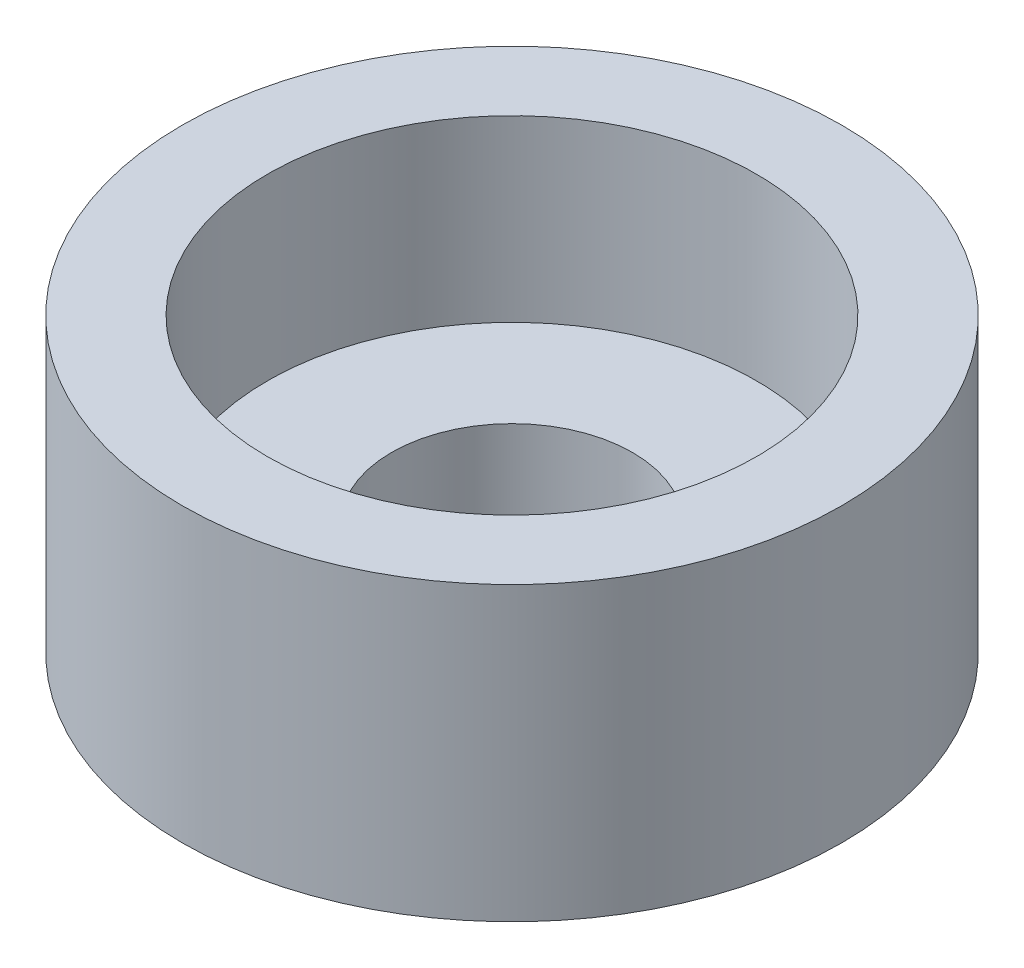
SolidWorks part; units mm, degrees
ref_plane "Front Plane" through (0, 0, 0) normal (0, 0, 1) x (1, 0, 0)
ref_plane "Top Plane" through (0, 0, 0) normal (0, 1, 0) x (1, 0, 0)
ref_plane "Right Plane" through (0, 0, 0) normal (1, 0, 0) x (0, 0, -1)
sketch "Sketch1" plane through (0, 0, 0) normal (0, 1, 0) x (1, 0, 0)
  circle A0 centre (0, 0) radius 35
  circle A1 centre (0, 0) radius 12.8
  dimension "D1" = 70
  dimension "D2" = 25.6
extrude "Boss-Extrude1" add sketch "Sketch1" along normal blind 31
sketch "Sketch4" plane through (0, 31, 0) normal (0, 1, 0) x (1, 0, 0)
  circle A0 centre (0, 0) radius 25.97
  dimension "D1" = 51.94
extrude "Cut-Extrude3" cut sketch "Sketch4" against normal blind 19
sketch "Sketch10" plane through (0, 0, 0) normal (0, -1, 0) x (1, 0, 0)
  line L0 (0, 0) -> (11.4907, 22.6522)
  line L1 (0, 0) -> (13.8721, -21.2774)
  line L2 (0, 0) -> (-25.3628, -1.3749)
  circle A0 centre (0, 0) radius 25.4
  circle A1 centre (-25.3628, -1.3749) radius 3.025
  circle A2 centre (11.4907, 22.6522) radius 3.025
  circle A3 centre (13.8721, -21.2774) radius 3.025
  dimension "D1" = 120
  dimension "D3" = 6.05
  dimension "D4" = 6.05
  dimension "D5" = 6.05
  dimension "D6" = 50.8
  dimension "D2" = 120
  dimension "D7" = 25.3628
extrude "Cut-Extrude6" cut sketch "Sketch10" against normal blind 5.1 contours A0 A1 | L2 A1 A0 | A0 A1 L2 | A0 A2 L0 | L0 A2 A0 | A0 A2 | L1 A3 A0 | A0 A3 L1 | A0 A3
